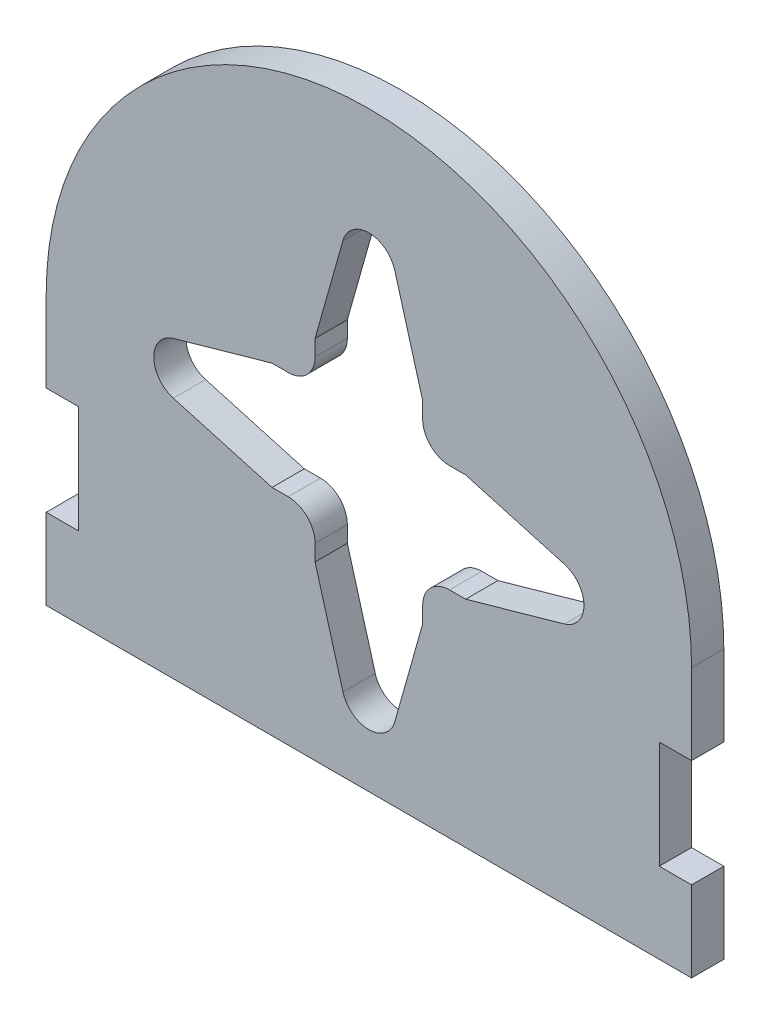
SolidWorks part; units mm, degrees
ref_plane "Front Plane" through (0, 0, 0) normal (0, 0, 1) x (1, 0, 0)
ref_plane "Top Plane" through (0, 0, 0) normal (0, 1, 0) x (1, 0, 0)
ref_plane "Right Plane" through (0, 0, 0) normal (1, 0, 0) x (0, 0, -1)
sketch "Sketch1" plane through (0, 0, 0) normal (0, 0, 1) x (1, 0, 0)
  line L0 (0, 0) -> (60, 0)
  line L1 (60, 0) -> (60, 25)
  line L2 (0, 0) -> (0, 25)
  line L3 (37.5, 20) -> (39, 20)
  line L4 (35, 16) -> (35, 17.5)
  line L5 (32.4058, 6.8201) -> (35, 16)
  line L6 (25, 16) -> (27.5942, 6.8201)
  line L7 (25, 17.5) -> (25, 16)
  line L8 (21, 20) -> (22.5, 20)
  line L9 (11.8201, 22.5942) -> (21, 20)
  line L10 (21, 30) -> (11.8201, 27.4058)
  line L11 (22.5, 30) -> (21, 30)
  line L12 (25, 34) -> (25, 32.5)
  line L13 (27.5942, 43.1799) -> (25, 34)
  line L14 (35, 34) -> (32.4058, 43.1799)
  line L15 (35, 32.5) -> (35, 34)
  line L16 (39, 30) -> (37.5, 30)
  line L17 (48.1799, 27.4058) -> (39, 30)
  line L18 (39, 20) -> (48.1799, 22.5942)
  line L19 (12.5, 25) -> (47.5, 25) construction
  line L20 (30, 42.5) -> (30, 7.5) construction
  arc A0 (60, 25) -> (0, 25) centre (30, 25) ccw
  arc A1 (37.5, 20) -> (35, 17.5) centre (37.5, 17.5) ccw
  arc A2 (27.5942, 6.8201) -> (32.4058, 6.8201) centre (30, 7.5) ccw
  arc A3 (25, 17.5) -> (22.5, 20) centre (22.5, 17.5) ccw
  arc A4 (11.8201, 27.4058) -> (11.8201, 22.5942) centre (12.5, 25) ccw
  arc A5 (22.5, 30) -> (25, 32.5) centre (22.5, 32.5) ccw
  arc A6 (32.4058, 43.1799) -> (27.5942, 43.1799) centre (30, 42.5) ccw
  arc A7 (35, 32.5) -> (37.5, 30) centre (37.5, 32.5) ccw
  arc A8 (48.1799, 22.5942) -> (48.1799, 27.4058) centre (47.5, 25) ccw
  point P3 (30, 25)
  point P39 (30, 25)
  point P40 (0, 0)
  point P41 (0, 0)
  point P42 (62.569, 43.5139)
  point P43 (60.9943, 43.7589)
  point P44 (85.027, 39.6194)
  point P45 (70.027, 39.6194)
  point P46 (62.9251, 35.5074)
  point P47 (0, 0)
  dimension "D3" = 2.5
  dimension "D1" = 25
  dimension "D2" = 60
  dimension "D4" = 35
  dimension "D5" = 1.5
  dimension "D6" = 5
  dimension "D7" = 5
extrude "Boss-Extrude1" add sketch "Sketch1" along normal blind 3
sketch "Sketch2" plane through (0, 0, 0) normal (0, 0, -1) x (-1, 0, 0)
  line L5 (-60, 0) -> (-60, 25) construction
  line L6 (-60, 7.5) -> (-57, 7.5)
  line L7 (-60, 7.5) -> (-60, 17.5)
  line L8 (-60, 17.5) -> (-57, 17.5)
  line L9 (-57, 7.5) -> (-57, 17.5)
  line L10 (-30, 0) -> (-30, 55) construction
  line L11 (0, 0) -> (-60, 0) construction
  line L13 (-3, 7.5) -> (-3, 17.5)
  line L14 (0, 17.5) -> (-3, 17.5)
  line L15 (0, 7.5) -> (0, 17.5)
  line L16 (0, 7.5) -> (-3, 7.5)
  arc A0 (0, 25) -> (-60, 25) centre (-30, 25) ccw construction
  point P13 (-60, 12.5)
  point P14 (-60, 12.5)
  dimension "D1" = 3
  dimension "D2" = 10
extrude "Cut-Extrude1" cut sketch "Sketch2" against normal through all
ref_plane "Plane1" through (30, 0, 0) normal (-1, 0, 0) x (0, 0, 1)
